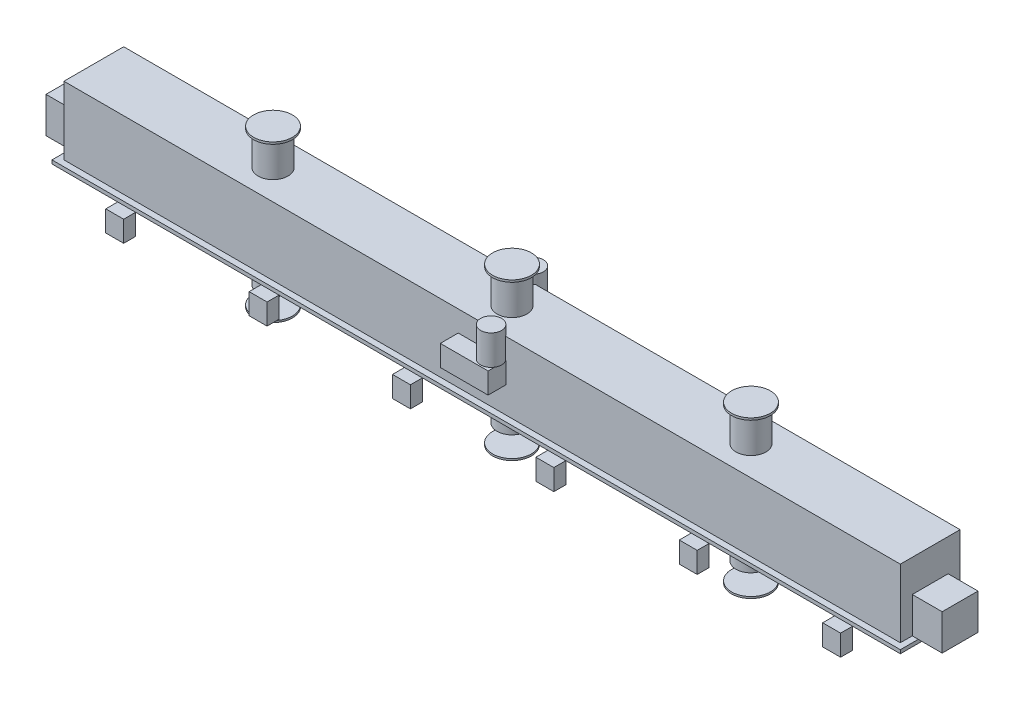
SolidWorks part; units mm, degrees
ref_plane "Front Plane" through (0, 0, 0) normal (0, 0, 1) x (1, 0, 0)
ref_plane "Top Plane" through (0, 0, 0) normal (0, 1, 0) x (1, 0, 0)
ref_plane "Right Plane" through (0, 0, 0) normal (1, 0, 0) x (0, 0, -1)
other "Configuration Table"
sketch "Sketch1" plane through (0, 0, 0) normal (0, 1, 0) x (1, 0, 0)
  line L1 (-7000, -500) -> (7000, -500)
  line L2 (-7000, -500) -> (-7000, 500)
  line L3 (-7000, 500) -> (7000, 500)
  line L4 (7000, -500) -> (7000, 500)
extrude "Boss-Extrude1" add sketch "Sketch1" along normal blind 500 flip side to cut
sketch "Sketch2" plane through (0, 0, 0) normal (0, 1, 0) x (1, 0, 0)
  circle A0 centre (-4000, 0) radius 250
  circle A1 centre (0, 0) radius 250
  circle A2 centre (4000, 0) radius 250
extrude "Boss-Extrude2" add sketch "Sketch2" along normal blind 350 from offset 500 flip side to cut
sketch "Sketch3" plane through (0, 0, 0) normal (0, 1, 0) x (1, 0, 0)
  circle A0 centre (-4000, 0) radius 325
  circle A1 centre (0, 0) radius 325
  circle A2 centre (4000, 0) radius 325
extrude "Boss-Extrude3" add sketch "Sketch3" along normal blind 30 from offset 820 flip side to cut
sketch "Sketch4" plane through (0, 0, 0) normal (0, 1, 0) x (1, 0, 0)
  line L1 (-7100, -600) -> (7100, -600)
  line L2 (-7100, -600) -> (-7100, 600)
  line L3 (-7100, 600) -> (7100, 600)
  line L4 (7100, -600) -> (7100, 600)
extrude "Boss-Extrude4" add sketch "Sketch4" along normal blind 60
sketch "Sketch5" plane through (0, 0, 0) normal (0, 1, 0) x (1, 0, 0)
  line L1 (-7000, -500) -> (7000, -500)
  line L2 (-7000, -500) -> (-7000, 500)
  line L3 (-7000, 500) -> (7000, 500)
  line L4 (7000, -500) -> (7000, 500)
extrude "Boss-Extrude5" add sketch "Sketch5" along normal blind 1140 from offset 60
sketch "Sketch6" plane through (0, 0, 0) normal (0, 1, 0) x (1, 0, 0)
  circle A0 centre (-4000, 0) radius 250
  circle A1 centre (0, 0) radius 250
  circle A2 centre (4000, 0) radius 250
extrude "Boss-Extrude6" add sketch "Sketch6" along normal blind 600 from offset 1200
sketch "Sketch7" plane through (0, 0, 0) normal (0, 1, 0) x (1, 0, 0)
  circle A0 centre (-4000, 0) radius 325
  circle A1 centre (0, 0) radius 325
  circle A2 centre (4000, 0) radius 325
extrude "Boss-Extrude7" add sketch "Sketch7" along normal blind 35 from offset 1765
sketch "Sketch8" plane through (0, 0, 0) normal (0, 1, 0) x (1, 0, 0)
  line L0 (-7000, -500) -> (-7000, 500) construction
  line L1 (-7500, -300) -> (-7000, -300)
  line L2 (-7500, -300) -> (-7500, 300)
  line L3 (-7500, 300) -> (-7000, 300)
  line L4 (-7000, -300) -> (-7000, 300)
  line L5 (7000, -500) -> (7000, 500) construction
  line L6 (7000, -300) -> (7500, -300)
  line L7 (7000, -300) -> (7000, 300)
  line L8 (7000, 300) -> (7500, 300)
  line L9 (7500, -300) -> (7500, 300)
extrude "Boss-Extrude8" add sketch "Sketch8" along normal blind 600 from offset 60
sketch "Sketch9" plane through (0, 0, 0) normal (0, 1, 0) x (1, 0, 0)
  line L1 (-400, -800) -> (400, -800)
  line L2 (-400, -800) -> (-400, 800)
  line L3 (-400, 800) -> (400, 800)
  line L4 (400, -800) -> (400, 800)
extrude "Boss-Extrude9" add sketch "Sketch9" along normal blind 350 from offset 500
sketch "Sketch10" plane through (0, 0, 0) normal (0, 1, 0) x (1, 0, 0)
  circle A0 centre (-250, 600) radius 175
  circle A1 centre (250, -600) radius 175
extrude "Boss-Extrude10" add sketch "Sketch10" along normal blind 500 from offset 850
sketch "Sketch11" plane through (0, 0, 0) normal (0, 1, 0) x (1, 0, 0)
  line L1 (-6150, -650) -> (-5850, -650)
  line L2 (-6150, -650) -> (-6150, -450)
  line L3 (-6150, -450) -> (-5850, -450)
  line L4 (-5850, -650) -> (-5850, -450)
  line L5 (-6150, 450) -> (-5850, 450)
  line L6 (-6150, 450) -> (-6150, 650)
  line L7 (-6150, 650) -> (-5850, 650)
  line L8 (-5850, 450) -> (-5850, 650)
  line L9 (-3750, -650) -> (-3450, -650)
  line L10 (-3750, -650) -> (-3750, -450)
  line L11 (-3750, -450) -> (-3450, -450)
  line L12 (-3450, -650) -> (-3450, -450)
  line L13 (-3750, 450) -> (-3450, 450)
  line L14 (-3750, 450) -> (-3750, 650)
  line L15 (-3750, 650) -> (-3450, 650)
  line L16 (-3450, 450) -> (-3450, 650)
  line L17 (-1350, -650) -> (-1050, -650)
  line L18 (-1350, -650) -> (-1350, -450)
  line L19 (-1350, -450) -> (-1050, -450)
  line L20 (-1050, -650) -> (-1050, -450)
  line L21 (-1350, 450) -> (-1050, 450)
  line L22 (-1350, 450) -> (-1350, 650)
  line L23 (-1350, 650) -> (-1050, 650)
  line L24 (-1050, 450) -> (-1050, 650)
  line L25 (1050, -650) -> (1350, -650)
  line L26 (1050, -650) -> (1050, -450)
  line L27 (1050, -450) -> (1350, -450)
  line L28 (1350, -650) -> (1350, -450)
  line L29 (1050, 450) -> (1350, 450)
  line L30 (1050, 450) -> (1050, 650)
  line L31 (1050, 650) -> (1350, 650)
  line L32 (1350, 450) -> (1350, 650)
  line L33 (3450, -650) -> (3750, -650)
  line L34 (3450, -650) -> (3450, -450)
  line L35 (3450, -450) -> (3750, -450)
  line L36 (3750, -650) -> (3750, -450)
  line L37 (3450, 450) -> (3750, 450)
  line L38 (3450, 450) -> (3450, 650)
  line L39 (3450, 650) -> (3750, 650)
  line L40 (3750, 450) -> (3750, 650)
  line L41 (5850, -650) -> (6150, -650)
  line L42 (5850, -650) -> (5850, -450)
  line L43 (5850, -450) -> (6150, -450)
  line L44 (6150, -650) -> (6150, -450)
  line L45 (5850, 450) -> (6150, 450)
  line L46 (5850, 450) -> (5850, 650)
  line L47 (5850, 650) -> (6150, 650)
  line L48 (6150, 450) -> (6150, 650)
extrude "Boss-Extrude11" add sketch "Sketch11" along normal blind 350 from offset 500 flip side to cut
